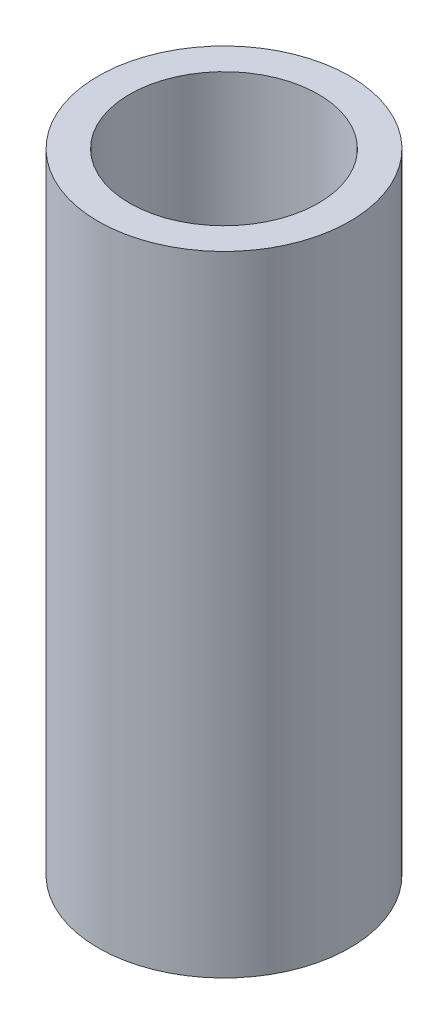
SolidWorks part; units mm, degrees
ref_plane "Front Plane" through (0, 0, 0) normal (0, 0, 1) x (1, 0, 0)
ref_plane "Top Plane" through (0, 0, 0) normal (0, 1, 0) x (1, 0, 0)
ref_plane "Right Plane" through (0, 0, 0) normal (1, 0, 0) x (0, 0, -1)
sketch "Sketch1" plane through (0, 0, 0) normal (0, 1, 0) x (1, 0, 0)
  circle A0 centre (0, 0) radius 10.16
  circle A1 centre (0, 0) radius 7.62
extrude "Boss-Extrude1" add sketch "Sketch1" along normal blind 50.8
